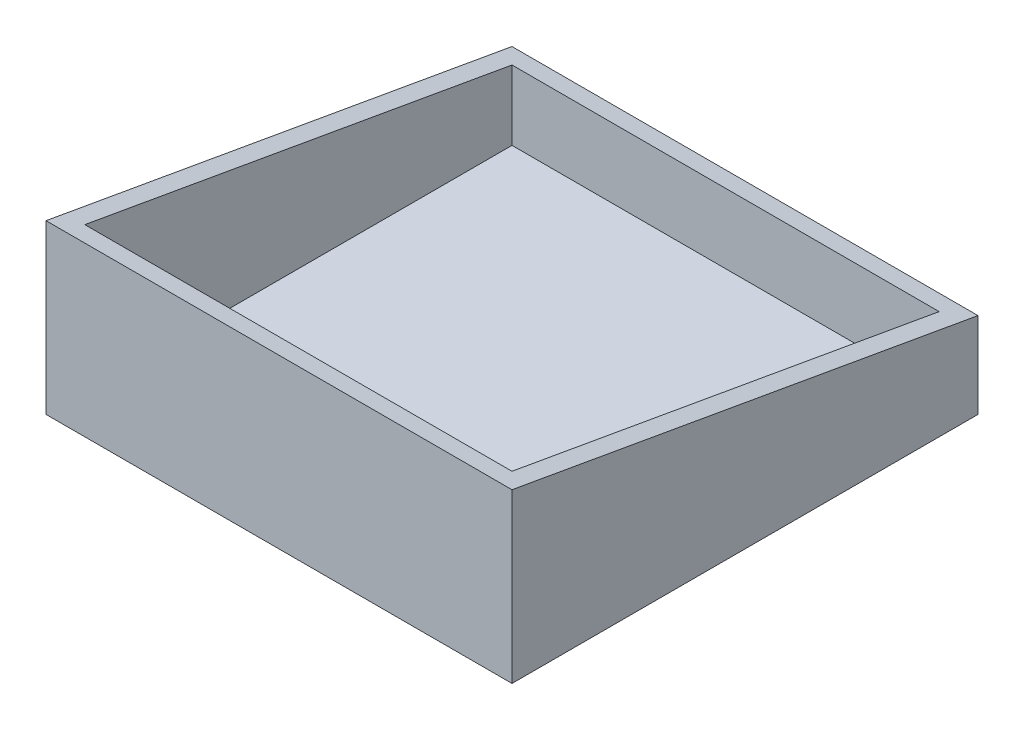
SolidWorks part; units mm, degrees
ref_plane "Front Plane" through (0, 0, 0) normal (0, 0, 1) x (1, 0, 0)
ref_plane "Top Plane" through (0, 0, 0) normal (0, 1, 0) x (1, 0, 0)
ref_plane "Right Plane" through (0, 0, 0) normal (1, 0, 0) x (0, 0, -1)
sketch "Sketch1" plane through (0, 0, 0) normal (1, 0, 0) x (0, 0, -1)
  line L1 (0, 0) -> (304.8, 0)
  line L4 (304.8, 0) -> (304.8, 56)
  line L5 (0, 109.7445) -> (304.8, 56)
  line L6 (0, 109.7445) -> (0, 0)
  dimension "D1" = 304.8
  dimension "D2" = 10
  dimension "D3" = 56
extrude "Boss-Extrude1" add sketch "Sketch1" along normal blind 304.8
shell "Shell1" thickness 12.7
